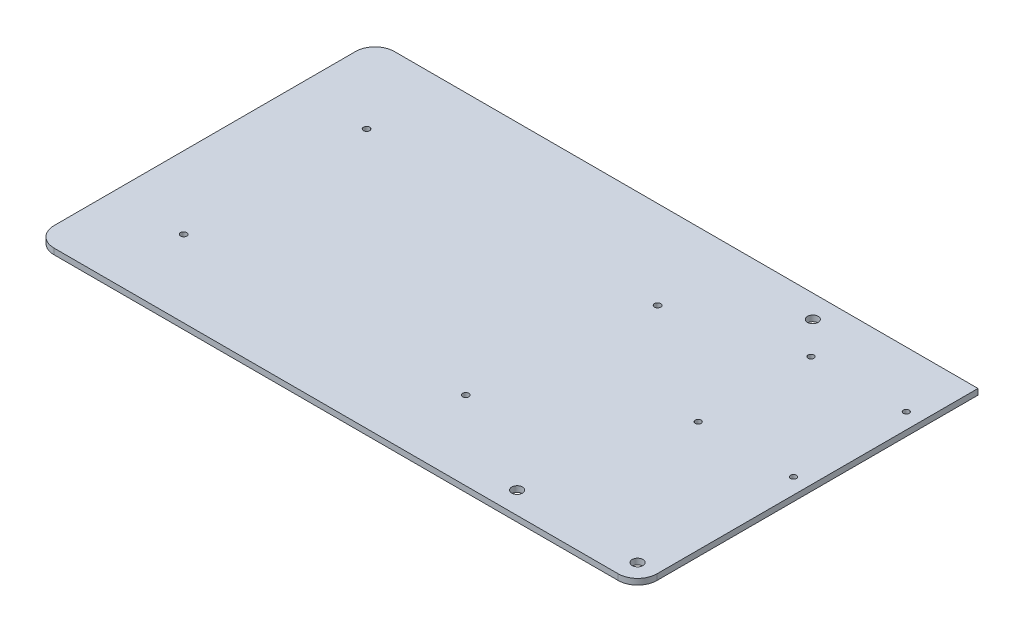
SolidWorks part; units mm, degrees
material "Custom Plastic"
ref_plane "Plan de face" through (0, 0, 0) normal (0, 0, 1) x (1, 0, 0)
ref_plane "Plan de dessus" through (0, 0, 0) normal (0, 1, 0) x (1, 0, 0)
ref_plane "Plan de droite" through (0, 0, 0) normal (1, 0, 0) x (0, 0, -1)
sketch "Esquisse1" plane through (0, 0, 0) normal (0, 1, 0) x (1, 0, 0)
  line L0 (-136.1429, 92.5) -> (163.8571, 92.5)
  line L1 (-146.1429, 92.5) -> (163.8571, 92.5) construction
  line L2 (-146.1429, 92.5) -> (-146.1429, -82.5) construction
  line L3 (-146.1429, -82.5) -> (163.8571, -82.5) construction
  line L4 (163.8571, 92.5) -> (163.8571, -82.5) construction
  line L5 (-146.1429, 92.5) -> (163.8571, -82.5) construction
  line L6 (-146.1429, -82.5) -> (163.8571, 92.5) construction
  line L7 (163.8571, 92.5) -> (163.8571, -72.5)
  line L8 (153.8571, -82.5) -> (-136.1429, -82.5)
  line L9 (-146.1429, 82.5) -> (-146.1429, -72.5)
  line L11 (-136.1429, 92.5) -> (-136.1429, 82.5) construction
  line L12 (153.8571, -82.5) -> (153.8571, -72.5) construction
  line L13 (153.8571, -72.5) -> (163.8571, -72.5) construction
  line L14 (81.7862, 76) -> (81.7862, 80.8) construction
  line L15 (81.7862, 80.8) -> (90.6434, 80.8) construction
  line L16 (-146.1429, -72.5) -> (-136.1429, -72.5) construction
  line L17 (-136.1429, -72.5) -> (-136.1429, -82.5) construction
  line L18 (-136.1429, 82.5) -> (-146.1429, 82.5) construction
  line L20 (-146.1429, 5) -> (163.8571, 5.7288) construction
  line L21 (106.7781, 63.7288) -> (155.7781, 63.7288) construction
  line L22 (155.7781, 63.7288) -> (163.8571, 63.7288) construction
  line L24 (155.7781, 63.7288) -> (155.7781, 92.5) construction
  line L26 (163.8571, 63.7288) -> (106.7781, 63.7288) construction
  line L27 (155.7781, 63.7288) -> (155.7781, 5.7288) construction
  line L28 (155.7781, 5.7288) -> (163.8571, 5.7288) construction
  line L29 (106.7781, 63.7288) -> (106.7781, 5.7288) construction
  line L30 (155.7781, 5.7288) -> (106.7781, 5.7288) construction
  line L31 (106.7781, 5.7288) -> (155.7781, 5.7288) construction
  line L32 (155.7781, 63.7288) -> (155.7781, 5.7288) construction
  line L33 (153.8571, -72.5) -> (90.6434, -71.2) construction
  arc A0 (-146.1429, 82.5) -> (-136.1429, 92.5) centre (-136.1429, 82.5) cw
  arc A1 (-146.1429, -72.5) -> (-136.1429, -82.5) centre (-136.1429, -72.5) ccw
  arc A3 (163.8571, -72.5) -> (153.8571, -82.5) centre (153.8571, -72.5) cw
  circle A18 centre (106.7781, 63.7288) radius 1.5
  circle A21 centre (155.7781, 63.7288) radius 1.5
  circle A22 centre (106.7781, 5.7288) radius 1.5
  circle A24 centre (90.6434, 80.8) radius 2.75
  circle A27 centre (155.7781, 5.7288) radius 1.5
  circle A32 centre (153.8571, -72.5) radius 2.75
  circle A33 centre (90.6434, -71.2) radius 2.75
  point P4 (0, 0)
  point P18 (0, 0)
  dimension "D3" = 10
  dimension "D4" = 8.8571
  dimension "D5" = 5.5
  dimension "D7" = 5.5
  dimension "D1" = 4.8
  dimension "D2" = 175
  dimension "D6" = 8.0791
  dimension "D8" = 57.0791
  dimension "D20" = 310
extrude "Boss.-Extru.1" add sketch "Esquisse1" along normal blind 3
sketch "Sketch1" plane through (0, 3, 0) normal (0, 1, 0) x (1, 0, 0)
  line L0 (-146.1429, 82.5) -> (-146.1429, -72.5) construction
  line L1 (-146.1429, 82.5) -> (-146.1429, -72.5) construction
  line L3 (-146.1429, 5) -> (-108.8402, 50.8964) construction
  line L4 (-108.8402, 50.8964) -> (44.5257, 47.142) construction
  line L5 (44.5257, 47.142) -> (35.1328, -42.1235) construction
  line L6 (35.1328, -42.1235) -> (-108.9302, -43.0536) construction
  line L7 (-108.9302, -43.0536) -> (-146.1429, 5) construction
  line L8 (-136.1429, 92.5) -> (-155, 92.5) construction
  circle A1 centre (44.5257, 47.142) radius 1.6
  circle A2 centre (35.1328, -42.1235) radius 1.6
  circle A3 centre (-108.9302, -43.0536) radius 1.6
  circle A4 centre (-108.8402, 50.8964) radius 1.6
  point P1 (-146.1429, 5)
  dimension "D1" = 3.2
  dimension "D2" = 3.2
  dimension "D3" = 3.2
  dimension "D4" = 3.2
  dimension "D5" = 60.7777
  dimension "D6" = 59.1436
  dimension "D7" = 153.3659
  dimension "D8" = 89.7583
  dimension "D9" = 144.063
extrude "Cut-Extrude9" cut sketch "Sketch1" against normal blind 10
